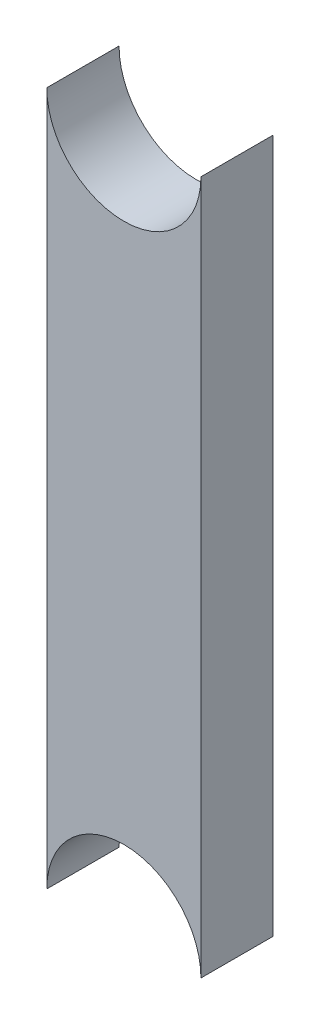
SolidWorks part; units mm, degrees
material "Titanium"
ref_plane "Front Plane" through (0, 0, 0) normal (0, 0, 1) x (1, 0, 0)
ref_plane "Top Plane" through (0, 0, 0) normal (0, 1, 0) x (1, 0, 0)
ref_plane "Right Plane" through (0, 0, 0) normal (1, 0, 0) x (0, 0, -1)
sketch "Sketch1" plane through (0, 0, 0) normal (0, 0, 1) x (1, 0, 0)
  line L1 (-3.2, 0) -> (-3.2, 28.8)
  line L2 (3.2, 28.8) -> (3.2, 0)
  line L3 (0, -1.65) -> (0, 1.65) construction
  arc A2 (3.2, 0) -> (-3.2, 0) centre (0, 0) ccw
  arc A3 (-3.2, 28.8) -> (3.2, 28.8) centre (0, 28.8) ccw
  dimension "D1" = 6.4
  dimension "D2" = 28.8
extrude "Boss-Extrude3" add sketch "Sketch1" along normal blind 3
equation "\"bScale\"= 8"
equation "\"lScale\"= 8"
equation "\"D2@Sketch1\"=3.6*\"lScale\""
equation "\"D1@Sketch1\"=.8*\"bScale\""
